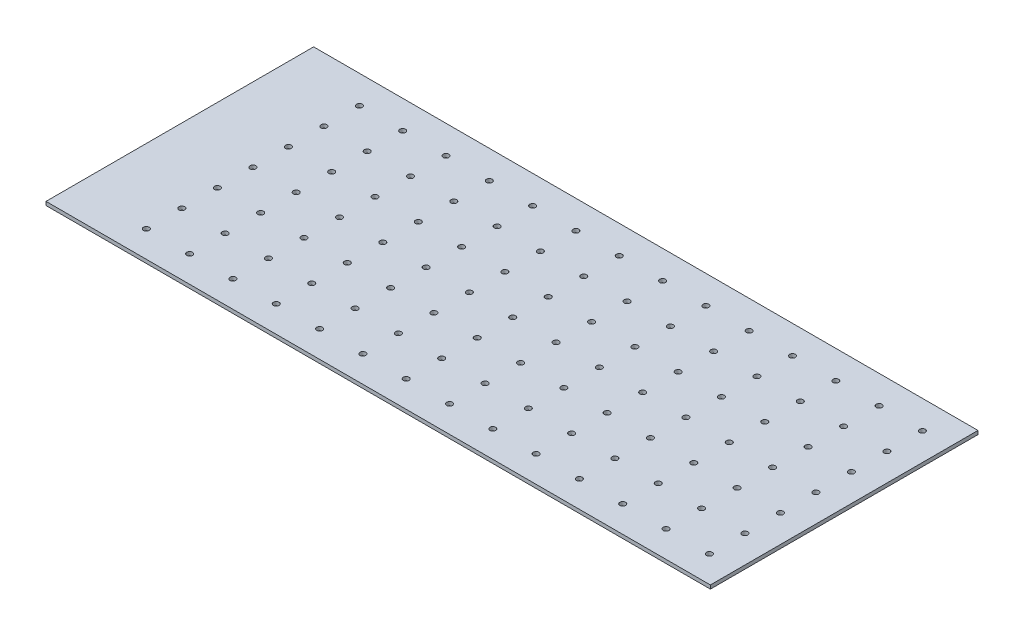
SolidWorks part; units mm, degrees
material "ABS PC"
ref_plane "Front Plane" through (0, 0, 0) normal (0, 0, 1) x (1, 0, 0)
ref_plane "Top Plane" through (0, 0, 0) normal (0, 1, 0) x (1, 0, 0)
ref_plane "Right Plane" through (0, 0, 0) normal (1, 0, 0) x (0, 0, -1)
sketch "Sketch1" plane through (0, 0, 0) normal (0, 1, 0) x (1, 0, 0)
  line L1 (-270, 116.82) -> (270, 116.82)
  line L2 (-270, 116.82) -> (-270, -116.82)
  line L3 (-270, -116.82) -> (270, -116.82)
  line L4 (270, 116.82) -> (270, -116.82)
  line L5 (-270, 116.82) -> (270, -116.82) construction
  line L6 (-270, -116.82) -> (270, 116.82) construction
  point P0 (0, 0)
  dimension "D1" = 540
  dimension "D2" = 233.64
extrude "Boss-Extrude1" add sketch "Sketch1" along normal blind 3.18
sketch "Sketch2" plane through (0, 3.18, 0) normal (0, 1, 0) x (1, 0, 0)
  line L0 (-270, 116.82) -> (-270, -116.82) construction
  line L1 (270, 116.82) -> (-270, 116.82) construction
  circle A0 centre (-245.45, 92.22) radius 2.5
  dimension "D1" = 5
  dimension "D2" = 24.55
  dimension "D3" = 24.6
extrude "Cut-Extrude1" cut sketch "Sketch2" against normal up to next
pattern_linear "LPattern1" count 14 spacing 37.81 along (1, 0, 0) count 7 spacing 31 along (0, 0, 1) of "Cut-Extrude1"
sketch "Sketch4" plane through (-270, 0, 0) normal (-1, 0, 0) x (0, 0, 1)
  line L1 (-116.82, 3.18) -> (116.82, 3.18)
  line L2 (-116.82, 3.18) -> (-116.82, 0)
  line L3 (-116.82, 0) -> (116.82, 0)
  line L4 (116.82, 3.18) -> (116.82, 0)
extrude "Boss-Extrude2" add sketch "Sketch4" along normal blind 40
